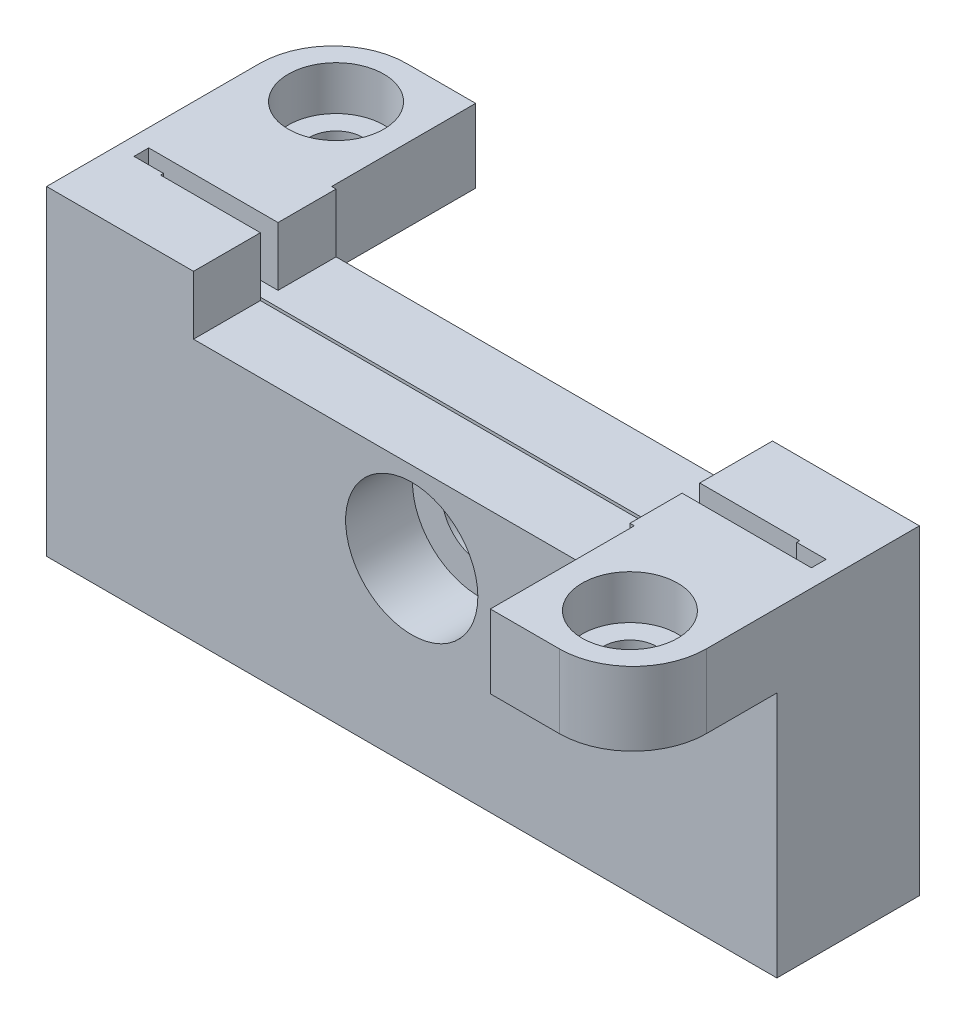
SolidWorks part; units mm, degrees
ref_plane "Front Plane" through (0, 0, 0) normal (0, 0, 1) x (1, 0, 0)
ref_plane "Top Plane" through (0, 0, 0) normal (0, 1, 0) x (1, 0, 0)
ref_plane "Right Plane" through (0, 0, 0) normal (1, 0, 0) x (0, 0, -1)
sketch "Sketch1" plane through (0, 0, 0) normal (0, 0, 1) x (1, 0, 0)
  line L0 (0, 0) -> (0, 21.8)
  line L1 (0, 21.8) -> (10, 21.8)
  line L2 (10, 21.8) -> (10, 17.8)
  line L3 (10, 17.8) -> (39.7, 17.8)
  line L4 (39.7, 17.8) -> (39.7, 21.8)
  line L5 (39.7, 21.8) -> (49.7, 21.8)
  line L6 (49.7, 21.8) -> (49.7, 0)
  line L7 (49.7, 0) -> (0, 0)
  point P9 (41.1125, 21.8)
  dimension "D1" = 21.8
  dimension "D2" = 49.7
  dimension "D3" = 4
  dimension "D4" = 10
extrude "Boss-Extrude1" add sketch "Sketch1" along normal mid plane 9.7
sketch "Sketch2" plane through (0, 21.8, 0) normal (0, 1, 0) x (1, 0, 0)
  line L0 (24.85, 4.85) -> (24.85, -4.85) construction
  line L1 (39.7, 4.85) -> (10, 4.85) construction
  line L2 (39.7, -4.85) -> (10, -4.85) construction
  line L4 (3.2, -0.3) -> (46.5, -0.3)
  line L5 (3.2, -0.3) -> (3.2, -0.1)
  line L6 (3.2, -0.1) -> (46.5, -0.1)
  line L7 (46.5, -0.3) -> (46.5, -0.1)
  line L8 (3.2, -0.3) -> (46.5, -0.1) construction
  line L9 (3.2, -0.1) -> (46.5, -0.3) construction
  point P6 (24.85, -0.2)
  point P11 (0, 0)
  point P12 (24.7843, -0.3943)
  point P13 (24.85, 0)
  point P14 (0, 0)
  dimension "D1" = 0.2
  dimension "D2" = 43.3
  dimension "D3" = 0.2
extrude "Cut-Extrude1" cut sketch "Sketch2" against normal blind 21
sketch "Sketch3" plane through (0, 21.8, 0) normal (0, 1, 0) x (1, 0, 0)
  line L6 (0, 4.85) -> (9.7, 4.85)
  line L8 (0, 4.85) -> (0, 9.65)
  line L9 (5, 14.65) -> (9.7, 14.65)
  line L11 (9.7, 4.85) -> (9.7, 14.65)
  line L12 (49.7, -4.85) -> (49.7, 4.85) construction
  line L13 (40, -4.85) -> (49.7, -4.85)
  line L14 (40, -4.85) -> (40, -14.65)
  line L15 (40, -14.65) -> (44.7, -14.65)
  line L16 (49.7, -4.85) -> (49.7, -9.65)
  line L17 (49.7, -4.85) -> (39.7, -4.85) construction
  arc A0 (44.7, -14.65) -> (49.7, -9.65) centre (44.7, -9.65) ccw
  arc A1 (0, 9.65) -> (5, 14.65) centre (5, 9.65) cw
  point P17 (0, 14.65)
  point P18 (0, 0)
  point P21 (0, 0)
  point P22 (0, 0)
  point P23 (40.6212, -4.85)
  point P26 (0, 0)
  dimension "D2" = 5
  dimension "D1" = 9.8
  dimension "D3" = 9.7
extrude "Boss-Extrude2" add sketch "Sketch3" against normal blind 5
sketch "Sketch5" plane through (0, 21.8, 0) normal (0, 1, 0) x (1, 0, 0)
  point P0 (44.85, -10)
  point P1 (4.85, 10)
  point P5 (0, 0)
  point P6 (0, 0)
  point P7 (4.85, 10)
  point P9 (44.85, -10)
hole_wizard "CBORE for M3 SHCS1" positions "Sketch5" profile "Sketch6" counterbore size "M3" standard "ANSI Metric" end condition up to next
sketch "Sketch6" plane through (44.85, 21.8, 10) normal (1, 0, 0) x (0, 0, 1)
  line L0 (0, 0) -> (0, 5)
  line L1 (0, 5) -> (1.8, 5)
  line L3 (1.8, 5) -> (1.8, 3)
  line L4 (1.8, 3) -> (3.25, 3)
  line L5 (3.25, 3) -> (3.25, 0)
  line L7 (3.25, 0) -> (0, 0)
  line L11 (0, -6.35) -> (0, 107.95) construction
  dimension "Thru Hole Dia." = 3.6
  dimension "Thru Hole Depth" = 5
  dimension "C'Bore Dia." = 6.5
  dimension "C'Bore Depth" = 3
sketch "Sketch7" plane through (0, 0, -4.85) normal (0, 0, -1) x (-1, 0, 0)
  line L0 (0, 0) -> (-49.7, 0) construction
  line L1 (-29.642, 12.3) -> (-27.246, 8.15)
  line L2 (-27.246, 8.15) -> (-22.454, 8.15)
  line L3 (-22.454, 8.15) -> (-20.058, 12.3)
  line L4 (-20.058, 12.3) -> (-22.454, 16.45)
  line L5 (-22.454, 16.45) -> (-27.246, 16.45)
  line L6 (-27.246, 16.45) -> (-29.642, 12.3)
  line L7 (-46.5, 0.8) -> (-3.2, 0.8) construction
  circle A0 centre (-24.85, 12.3) radius 4.15 construction
  point P1 (-25.2648, 5.9968)
  point P11 (-24.85, 0)
  dimension "D1" = 8.3
  dimension "D2" = 11.5
extrude "Cut-Extrude2" cut sketch "Sketch7" against normal blind 4
sketch "Sketch9" plane through (0, 0, 4.85) normal (0, 0, 1) x (1, 0, 0)
  circle A0 centre (24.85, 12.3) radius 4.5
  dimension "D1" = 9
extrude "Cut-Extrude3" cut sketch "Sketch9" against normal up to next
sketch "Sketch10" plane through (0, 21.8, 0) normal (0, 1, 0) x (1, 0, 0)
  line L0 (3.2, -0.1) -> (3.2, -0.3) construction
  line L1 (10, -0.1) -> (1.2, -0.1)
  line L2 (10, -0.1) -> (10, 0.9)
  line L3 (10, 0.9) -> (1.2, 0.9)
  line L4 (1.2, -0.1) -> (1.2, 0.9)
  line L5 (39.7, -0.3) -> (48.5, -0.3)
  line L6 (39.7, -0.3) -> (39.7, -1.3)
  line L7 (39.7, -1.3) -> (48.5, -1.3)
  line L8 (48.5, -0.3) -> (48.5, -1.3)
  dimension "D1" = 2
  dimension "D2" = 1
extrude "Cut-Extrude4" cut sketch "Sketch10" against normal up to surface (4 mm away) up to face at (24.85, 17.8, 2.575)
sketch "Sketch11" plane through (0, 0, 0.1) normal (0, 0, 1) x (1, 0, 0)
  circle A0 centre (24.85, 12.3) radius 2.7
  dimension "D1" = 5.4
extrude "Cut-Extrude5" cut sketch "Sketch11" against normal up to surface (0.95 mm away) up to face at (24.85, 12.3, -0.85)
